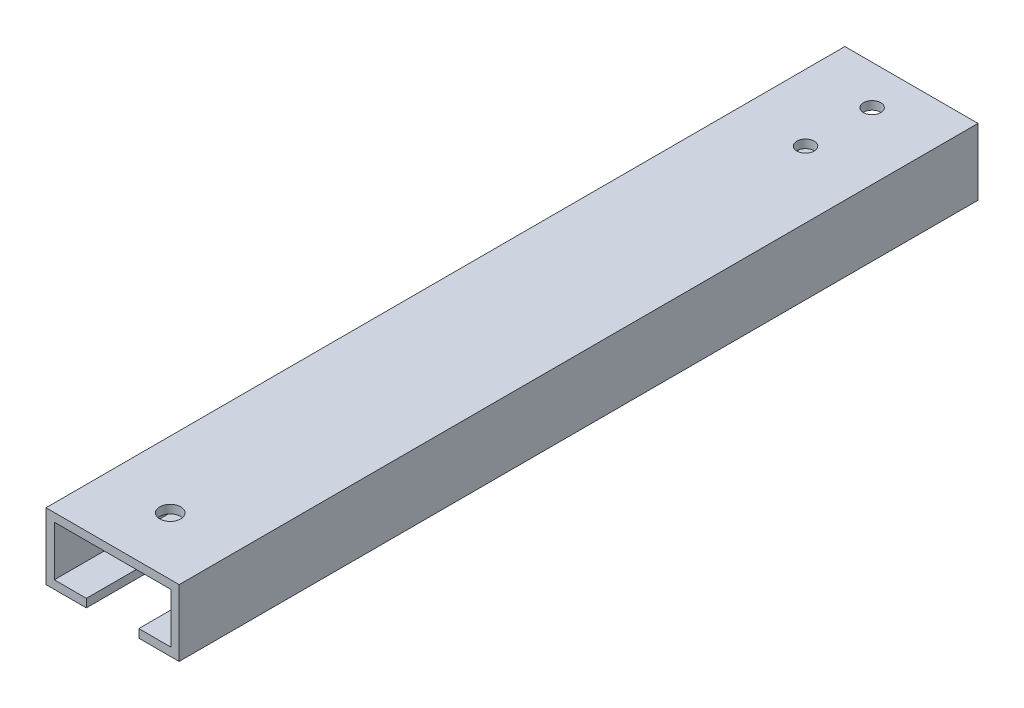
SolidWorks part; units mm, degrees
material "6061 Alloy"
ref_plane "Front Plane" through (0, 0, 0) normal (0, 0, 1) x (1, 0, 0)
ref_plane "Top Plane" through (0, 0, 0) normal (0, 1, 0) x (1, 0, 0)
ref_plane "Right Plane" through (0, 0, 0) normal (1, 0, 0) x (0, 0, -1)
sketch "Sketch1" plane through (0, 0, 0) normal (0, 0, 1) x (1, 0, 0)
  line L0 (-11.1125, 4.7625) -> (11.1125, 4.7625)
  line L2 (-12.7, 6.35) -> (12.7, 6.35)
  line L3 (-12.7, 6.35) -> (-12.7, -6.35)
  line L4 (-12.7, -6.35) -> (12.7, -6.35)
  line L5 (12.7, 6.35) -> (12.7, -6.35)
  line L10 (11.1125, 4.7625) -> (11.1125, -4.7625)
  line L11 (-11.1125, -4.7625) -> (11.1125, -4.7625)
  line L12 (-11.1125, 4.7625) -> (-11.1125, -4.7625)
  point P12 (0, 6.35)
  point P14 (12.7, 0)
  dimension "Wall Thickness" = 1.5875
  dimension "Outside Width" = 25.4
  dimension "Outside Height" = 12.7
  dimension "Inside Height" = 9.525
  dimension "Inside Width" = 22.225
sketch "Sketch2" plane through (0, 0, 0) normal (1, 0, 0) x (0, 0, -1)
  line L0 (304.8, 0) -> (-304.8, 0)
  point P4 (0, 0)
  point P7 (-304.8, 0)
  point P10 (304.8, 0)
  dimension "Length" = 609.6
sketch "Sketch3" plane through (0, 0, 0) normal (0, 0, 1) x (1, 0, 0)
  line L21 (12.7, 6.35) -> (-12.7, 6.35)
  line L22 (12.7, -6.35) -> (12.7, 6.35)
  line L23 (-12.7, -6.35) -> (12.7, -6.35)
  line L24 (-12.7, 6.35) -> (-12.7, -6.35)
  line L25 (12.7, 6.35) -> (-12.7, 6.35)
  line L26 (12.7, -6.35) -> (12.7, 6.35)
  line L27 (-12.7, -6.35) -> (12.7, -6.35)
  line L28 (-12.7, 6.35) -> (-12.7, -6.35)
  line L29 (11.1125, 4.7625) -> (-11.1125, 4.7625)
  line L30 (11.1125, -4.7625) -> (11.1125, 4.7625)
  line L31 (-11.1125, -4.7625) -> (11.1125, -4.7625)
  line L32 (-11.1125, 4.7625) -> (-11.1125, -4.7625)
  line L33 (11.1125, 4.7625) -> (-11.1125, 4.7625)
  line L34 (11.1125, -4.7625) -> (11.1125, 4.7625)
  line L35 (-11.1125, -4.7625) -> (11.1125, -4.7625)
  line L36 (-11.1125, 4.7625) -> (-11.1125, -4.7625)
  dimension "D1" = 0
  dimension "D2" = 0
extrude "Boss-Extrude1" add sketch "Sketch3" along normal blind 152.4
sketch "Drawing Reference" plane through (0, 0, 0) normal (1, 0, 0) x (0, 0, -1)
  line L0 (-304.8, 0) -> (304.8, 0) construction
  line L1 (-76.2, -6.35) -> (-76.2, 6.35) construction
  line L2 (-152.4, -6.35) -> (0, -6.35) construction
  line L5 (-152.4, 6.35) -> (0, 6.35) construction
  point P7 (-286.512, 0)
  point P8 (134.112, 0)
  dimension "D1" = 18.288
sketch "Sketch4" plane through (0, 6.35, 0) normal (0, 1, 0) x (1, 0, 0)
  line L0 (-12.7, -152.4) -> (-12.7, 0) construction
  line L1 (12.7, -152.4) -> (-12.7, -152.4) construction
  circle A0 centre (0, -141.4) radius 2
  dimension "D1" = 4
  dimension "D2" = 11
  dimension "D3" = 12.7
extrude "Cut-Extrude1" cut sketch "Sketch4" against normal up to surface (1.5875 mm away) up to face at (0, 4.7625, 76.2)
sketch "Sketch5" plane through (0, -6.35, 0) normal (0, -1, 0) x (1, 0, 0)
  circle A1 centre (-8, 141.4) radius 1.5004
  circle A2 centre (0, 149.4) radius 1.5004
  circle A3 centre (8, 141.4) radius 1.5004
  point P12 (0, 141.4)
extrude "Cut-Extrude2" cut sketch "Sketch5" against normal up to surface (1.5875 mm away) up to face at (0, -4.7625, 76.2)
sketch "Sketch6" plane through (0, -6.35, 0) normal (0, -1, 0) x (1, 0, 0)
  line L0 (-5, 152.4) -> (-5, 136.4)
  line L1 (-12.7, 152.4) -> (12.7, 152.4) construction
  line L2 (-5, 136.4) -> (5, 136.4)
  line L3 (5, 136.4) -> (5, 152.4)
  line L4 (-8, 141.4) -> (8, 141.4) construction
  line L5 (0, 149.4) -> (0, 127.1732) construction
  circle A0 centre (-8, 141.4) radius 1.5004 construction
  circle A1 centre (8, 141.4) radius 1.5004 construction
  circle A3 centre (0, 141.4) radius 5 construction
  point P18 (0, 141.4)
  dimension "D1" = 10
extrude "Cut-Extrude3" cut sketch "Sketch6" against normal blind 2.54 and the other way through all
ref_plane "Plane1" through (0, -6.35, 0) normal (0, -1, 0) x (-1, 0, 0)
sketch "Sketch7" plane through (0, -6.35, 0) normal (0, -1, 0) x (-1, 0, 0)
  line L0 (-12.7, -152.4) -> (-12.7, 0) construction
  line L1 (12.7, 0) -> (-12.7, 0) construction
  point P0 (0, -20.2)
  point P1 (0, -7.5)
  dimension "D1" = 12.7
  dimension "D2" = 12.7
  dimension "D3" = 20.2
  dimension "D4" = 7.5
hole_wizard "M4x0.7 Tapped Hole1" positions "Sketch8" profile "Sketch9" tap size "M4x0.7" standard "ANSI Metric" end condition through all
sketch "Sketch8" plane through (0, -6.35, 0) normal (0, -1, 0) x (-1, 0, 0)
  point P0 (0, -20.2)
  point P3 (0, -7.5)
sketch "Sketch9" plane through (0, -6.35, 20.2) normal (1, 0, 0) x (0, 0, -1)
  line L0 (0, 0) -> (0, 12.7)
  line L1 (0, 12.7) -> (1.65, 12.7)
  line L2 (1.65, 12.7) -> (1.65, 0)
  line L5 (1.65, 0) -> (0, 0)
  line L11 (0, -6.35) -> (0, 107.95) construction
  dimension "Thru Tap Drill Dia." = 3.3
  dimension "Thru Tap Drill Depth" = 12.7
equation "\"D1@Drawing Reference\"=\"Outside Width@Sketch1\" * 0.72"
